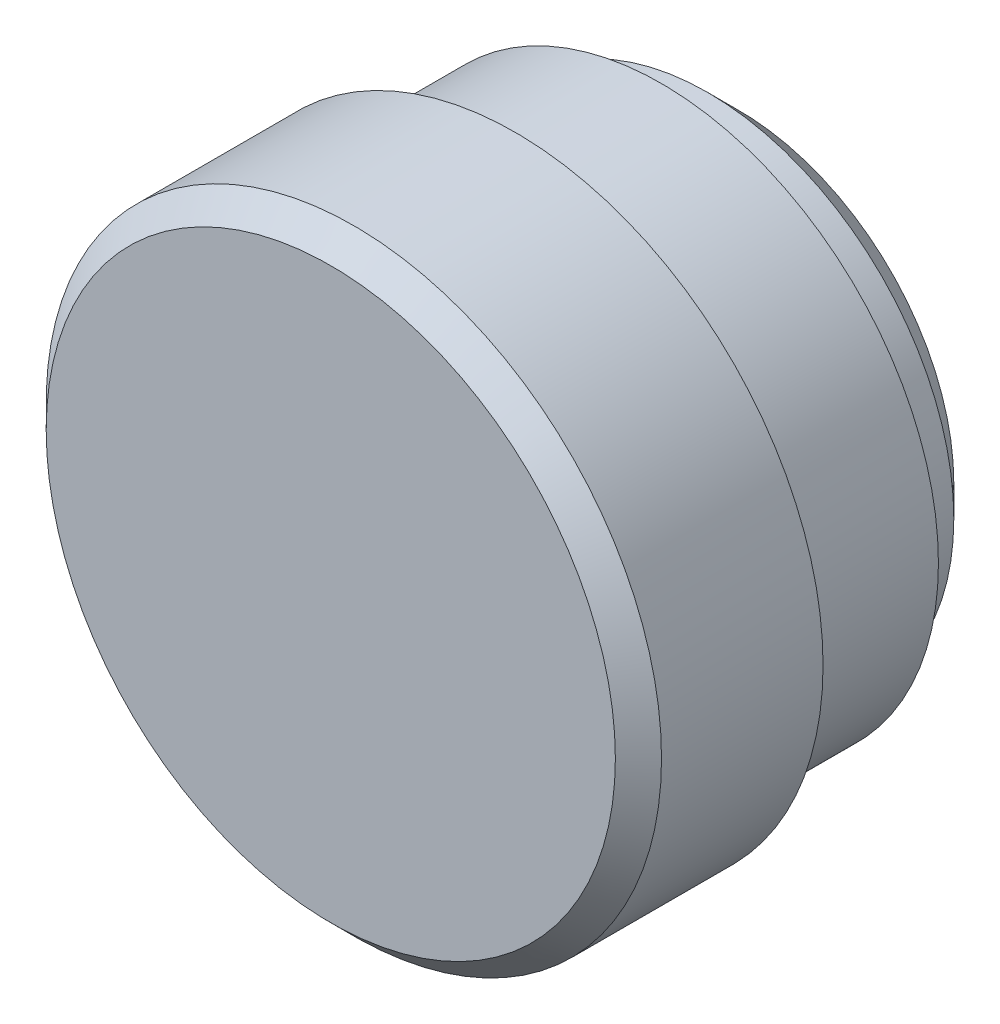
SolidWorks part; units mm, degrees
ref_plane "Plan de face" through (0, 0, 0) normal (0, 0, 1) x (1, 0, 0)
ref_plane "Plan de dessus" through (0, 0, 0) normal (0, 1, 0) x (1, 0, 0)
ref_plane "Plan de droite" through (0, 0, 0) normal (1, 0, 0) x (0, 0, -1)
sketch "Sketch1" plane through (0, 0, 0) normal (0, 0, 1) x (1, 0, 0)
  circle A0 centre (0, 0) radius 8
  dimension "D1" = 16
extrude "Boss-Extrude1" add sketch "Sketch1" along normal blind 2.5 contours A0
sketch "Sketch2" plane through (0, 0, 2.5) normal (0, 0, 1) x (1, 0, 0)
  circle A0 centre (0, 0) radius 9
  dimension "D1" = 18
extrude "Boss-Extrude2" add sketch "Sketch2" along normal blind 4.5
sketch "Sketch3" plane through (0, 0, 7) normal (0, 0, 1) x (1, 0, 0)
  circle A0 centre (0, 0) radius 8
  dimension "D1" = 16
extrude "Boss-Extrude3" add sketch "Sketch3" along normal blind 0.25
sketch "Sketch4" plane through (0, 0, 7.25) normal (0, 0, 1) x (1, 0, 0)
  circle A0 centre (0, 0) radius 10
  dimension "D1" = 20
extrude "Boss-Extrude4" add sketch "Sketch4" along normal blind 6
sketch "Sketch5" plane through (0, 0, 0) normal (0, 0, -1) x (-1, 0, 0)
  line L1 (-2.5, 2.5) -> (2.5, 2.5)
  line L2 (-2.5, 2.5) -> (-2.5, -2.5)
  line L3 (-2.5, -2.5) -> (2.5, -2.5)
  line L4 (2.5, 2.5) -> (2.5, -2.5)
  point P5 (2.5, 0)
  point P6 (0, 2.5)
  dimension "D1" = 5
  dimension "D2" = 5
extrude "Cut-Extrude1" cut sketch "Sketch5" against normal blind 5
chamfer "Chamfer1" distance 1 angle 45 1 edges at (8, 0, 0)
chamfer "Chamfer2" distance 0.75 angle 45 1 edges at (10, 0, 13.25)
